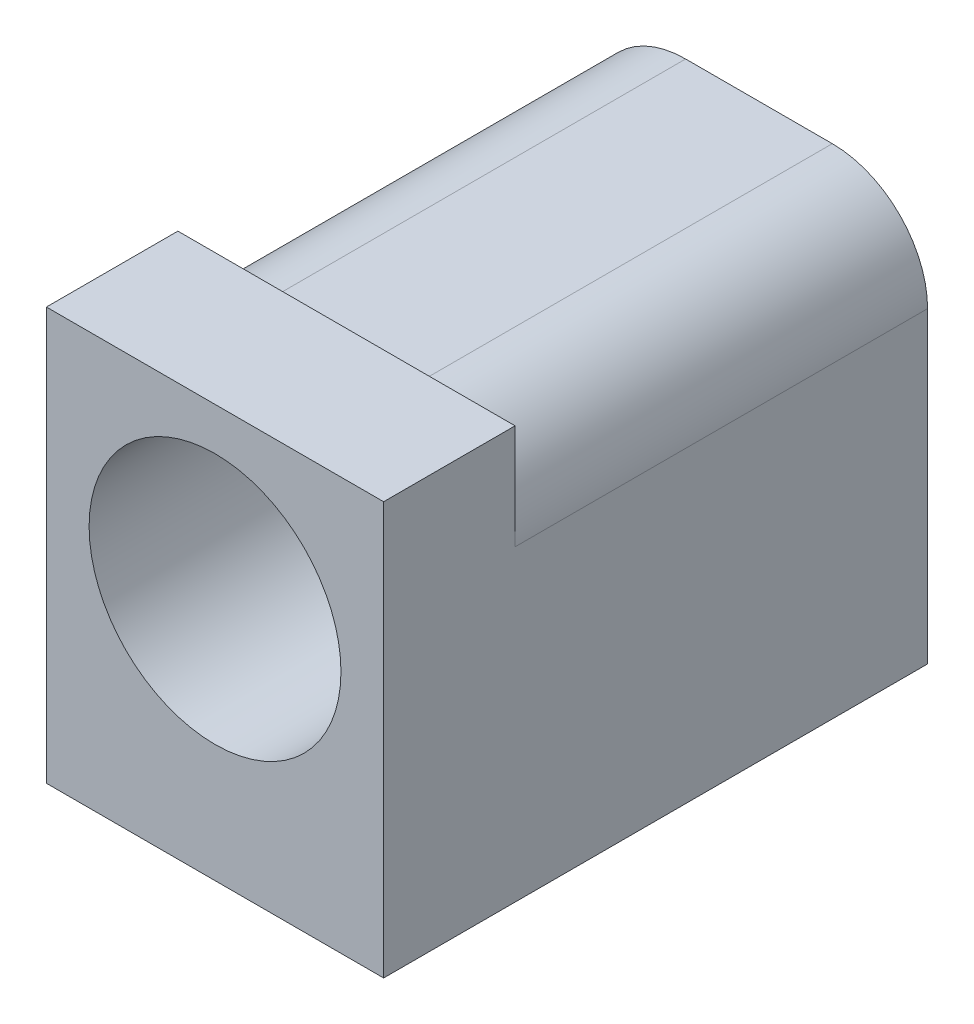
SolidWorks part; units mm, degrees
ref_plane "Front Plane" through (0, 0, 0) normal (0, 0, 1) x (1, 0, 0)
ref_plane "Top Plane" through (0, 0, 0) normal (0, 1, 0) x (1, 0, 0)
ref_plane "Right Plane" through (0, 0, 0) normal (1, 0, 0) x (0, 0, -1)
sketch "Sketch1" plane through (0, 0, 0) normal (0, 1, 0) x (1, 0, 0)
  line L1 (0, 0) -> (8.9916, 0)
  line L2 (0, 0) -> (0, 14.5034)
  line L3 (0, 14.5034) -> (8.9916, 14.5034)
  line L4 (8.9916, 0) -> (8.9916, 14.5034)
  dimension "D1" = 8.9916
  dimension "D2" = 14.5034
extrude "Boss-Extrude1" add sketch "Sketch1" along normal blind 10.9982
sketch "Sketch2" plane through (0, 0, 0) normal (0, 0, 1) x (1, 0, 0)
  line L0 (0, 0) -> (8.9916, 0) construction
  line L1 (0, 10.9982) -> (0, 0) construction
  line L2 (8.9916, 10.9982) -> (8.9916, 0) construction
  circle A0 centre (4.4958, 6.5024) radius 3.3577
  dimension "D1" = 6.5024
  dimension "D2" = 4.4958
  dimension "D3" = 4.4958
extrude "Cut-Extrude1" cut sketch "Sketch2" against normal blind 11.43
sketch "Sketch3" plane through (0, 10.9982, 0) normal (0, 1, 0) x (1, 0, 0)
  line L0 (8.9916, 0) -> (8.9916, 14.5034) construction
  line L1 (0, 14.5034) -> (8.9916, 14.5034)
  line L2 (0, 14.5034) -> (0, 3.5052)
  line L3 (0, 3.5052) -> (8.9916, 3.5052)
  line L4 (8.9916, 14.5034) -> (8.9916, 3.5052)
  line L5 (0, 0) -> (8.9916, 0) construction
  dimension "D1" = 3.5052
extrude "Cut-Extrude2" cut sketch "Sketch3" against normal blind 0.254
fillet "Fillet1" radius 2.54 1 edges at (8.9916, 10.7442, -9.0043)
fillet "Fillet2" radius 2.54 1 edges at (0, 10.7442, -9.0043)
